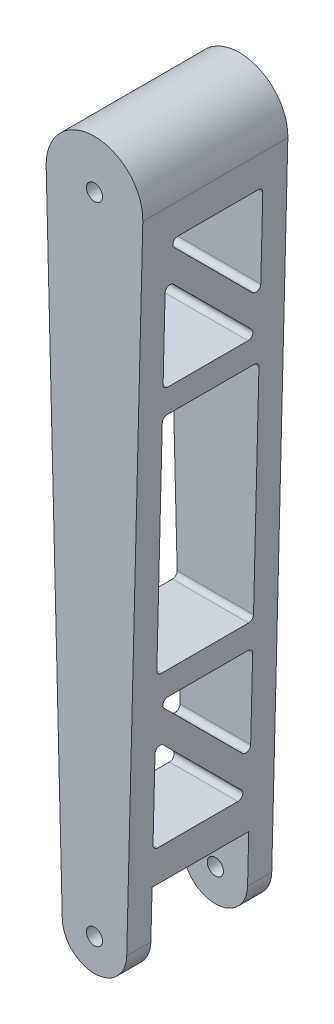
SolidWorks part; units mm, degrees
ref_plane "前视基准面" through (0, 0, 0) normal (0, 0, 1) x (1, 0, 0)
ref_plane "上视基准面" through (0, 0, 0) normal (0, 1, 0) x (1, 0, 0)
ref_plane "右视基准面" through (0, 0, 0) normal (1, 0, 0) x (0, 0, -1)
sketch "草图1" plane through (0, 0, 0) normal (0, 0, 1) x (1, 0, 0)
  line L0 (0, 0) -> (0, -55.5842) construction
  line L1 (-29.9906, -0.75) -> (-19.9937, -400.5)
  line L2 (29.9906, -0.75) -> (19.9937, -400.5)
  arc A0 (29.9906, -0.75) -> (-29.9906, -0.75) centre (0, 0) ccw
  arc A1 (-19.9937, -400.5) -> (19.9937, -400.5) centre (0, -400) ccw
  circle A2 centre (0, 0) radius 5
  circle A3 centre (0, -400) radius 5
  dimension "D1" = 60
  dimension "D2" = 40
  dimension "D4" = 10
  dimension "D5" = 10
  dimension "D3" = 400
extrude "凸台-拉伸1" add sketch "草图1" along normal blind 90 contours L2 A1 L1 A0 | A2 | A3
sketch "草图2" plane through (0, 0, 0) normal (1, 0, 0) x (0, 0, -1)
  line L0 (-45, 40.8352) -> (-45, -400.5) construction
  line L1 (-75, -370.75) -> (-15, -370.75)
  line L2 (-75, -370.75) -> (-75, -520.75)
  line L3 (-75, -520.75) -> (-15, -520.75)
  line L4 (-15, -370.75) -> (-15, -520.75)
  line L5 (0, -0.75) -> (0, -400.5) construction
  line L6 (-90, -0.75) -> (-90, -400.5) construction
  line L7 (-90, -400.5) -> (0, -400.5) construction
  line L8 (-75, -20) -> (-15, -20)
  line L9 (-15, -20) -> (-15, -80)
  line L10 (-15, -80) -> (-75, -20)
  line L11 (-75, -40) -> (-75, -100)
  line L12 (-75, -100) -> (-15, -100)
  line L13 (-15, -100) -> (-75, -40)
  line L14 (-15, -330.75) -> (-75, -270.75)
  line L15 (-75, -270.75) -> (-15, -270.75)
  line L16 (-15, -270.75) -> (-15, -330.75)
  line L17 (-15, -350.75) -> (-75, -290.75)
  line L18 (-75, -290.75) -> (-75, -350.75)
  line L19 (-75, -350.75) -> (-15, -350.75)
  line L21 (-75, -115) -> (-15, -115)
  line L22 (-75, -115) -> (-75, -255.75)
  line L23 (-75, -255.75) -> (-15, -255.75)
  line L24 (-15, -115) -> (-15, -255.75)
  dimension "D1" = 60
  dimension "D2" = 370
  dimension "D3" = 150
  dimension "D4" = 60
  dimension "D5" = 20
  dimension "D6" = 60
  dimension "D7" = 80
  dimension "D8" = 60
  dimension "D9" = 2
  dimension "D10" = 15
  dimension "D11" = 15
  dimension "D12" = 60
  dimension "D13" = 20
extrude "切除-拉伸1" cut sketch "草图2" against normal through all both and the other way through all
fillet "圆角1" radius 3 16 edges at (0, -115, 15) (0, -255.75, 15) (0, -255.75, 75) (0, -115, 75) (0, -100, 75) (0, -40, 75) (0, -100, 15) (0, -80, 15) (0, -20, 15) (0, -20, 75) (0, -350.75, 75) (0, -290.75, 75) (0, -350.75, 15) (0, -330.75, 15) (0, -270.75, 75) (0, -270.75, 15)
